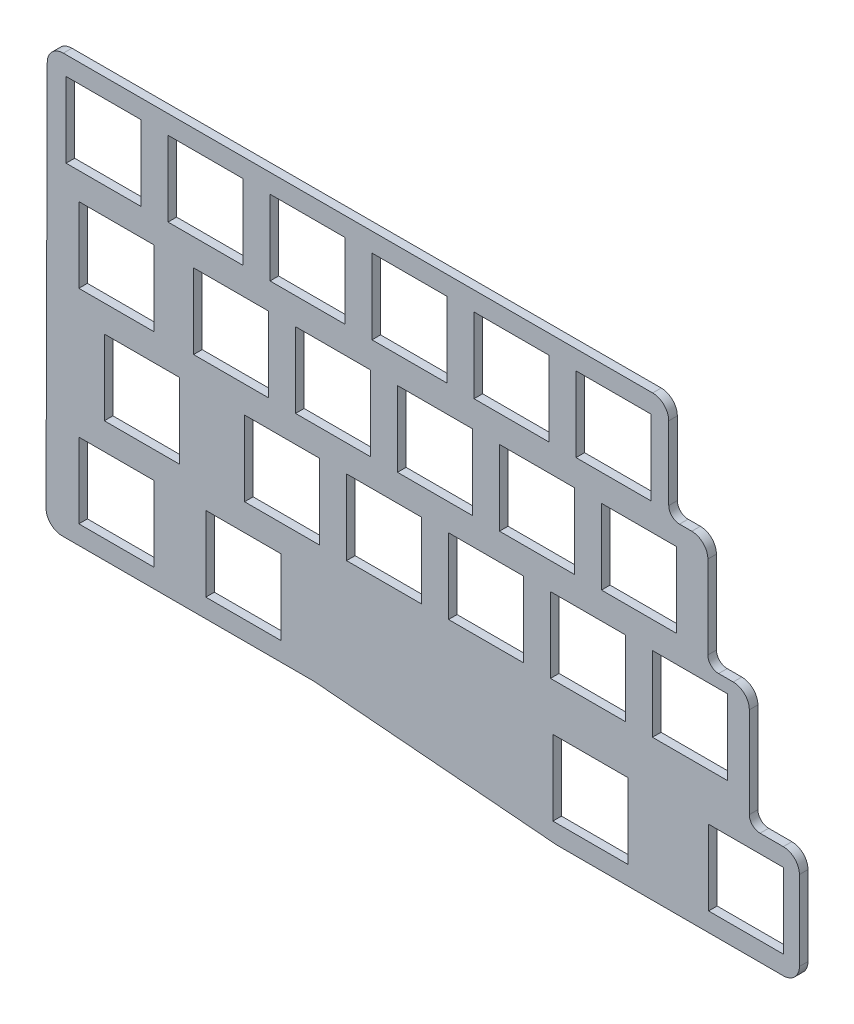
SolidWorks part; units mm, degrees
ref_plane "Front Plane" through (0, 0, 0) normal (0, 0, 1) x (1, 0, 0)
ref_plane "Top Plane" through (0, 0, 0) normal (0, 1, 0) x (1, 0, 0)
ref_plane "Right Plane" through (0, 0, 0) normal (1, 0, 0) x (0, 0, -1)
sketch "Sketch1" plane through (0, 0, 0) normal (0, 0, 1) x (1, 0, 0)
  line B0 (69.2565, 39.1549) -> (-80.7031, 39.0588)
  line B1 (9.8084, 35.5569) -> (-4.1916, 35.5569)
  line B2 (14.8084, 35.5569) -> (14.8084, 21.5569)
  line B3 (28.8084, 21.5569) -> (28.8084, 35.5569)
  line B4 (-28.1916, 35.5569) -> (-42.1916, 35.5569)
  circle B5 centre (35.1084, 34.2569) radius 1.5
  line B6 (28.8084, 35.5569) -> (14.8084, 35.5569)
  line B7 (-9.1916, 21.5569) -> (-9.1916, 35.5569)
  line B8 (-9.1916, 35.5569) -> (-23.1916, 35.5569)
  line B9 (-83.7012, 36.0684) -> (-83.9319, -35.9335)
  line B10 (-63.8166, 16.5569) -> (-77.8166, 16.5569)
  line B11 (-42.4416, 2.5569) -> (-42.4416, 16.5569)
  line B12 (-23.4416, 2.5569) -> (-23.4416, 16.5569)
  line B13 (-18.4416, 16.5569) -> (-18.4416, 2.5569)
  line B14 (-46.9416, -2.4431) -> (-46.9416, -16.4431)
  line B15 (-32.9416, -16.4431) -> (-32.9416, -2.4431)
  line B16 (5.0584, -2.4431) -> (-8.9416, -2.4431)
  line B17 (19.5584, 2.5569) -> (33.5584, 2.5569)
  line B18 (33.5584, 2.5569) -> (33.5584, 16.5569)
  line B19 (-77.8166, 16.5569) -> (-77.8166, 2.5569)
  line B20 (-8.9416, -2.4431) -> (-8.9416, -16.4431)
  line B21 (5.0584, -16.4431) -> (5.0584, -2.4431)
  line B22 (29.0584, -16.4431) -> (43.0584, -16.4431)
  line B23 (62.4422, -40.6918) -> (72.1045, -11.705)
  line B24 (10.5084, -25.2431) -> (10.5084, -39.2431)
  line B25 (-63.8166, -21.4431) -> (-77.8166, -21.4431)
  line B26 (-66.1916, 21.5569) -> (-66.1916, 35.5569)
  line B27 (-66.1916, 35.5569) -> (-80.1916, 35.5569)
  line B28 (-80.1916, 35.5569) -> (-80.1916, 21.5569)
  arc B29 (-80.7031, 39.0588) -> (-83.7012, 36.0684) centre (-80.7012, 36.0588) ccw
  arc B30 (-83.9319, -35.9335) -> (-80.932, -38.9431) centre (-80.932, -35.9431) ccw
  line B31 (-80.932, -38.9431) -> (-34.1624, -38.9431)
  arc B32 (-33.9113, -38.9537) -> (-34.1624, -38.9431) centre (-34.1624, -41.9431) ccw
  line B33 (-33.9113, -38.9537) -> (11.0831, -42.7326)
  arc B34 (11.0831, -42.7326) -> (11.3342, -42.7431) centre (11.3342, -39.7431) ccw
  line B35 (11.3342, -42.7431) -> (59.5961, -42.7431)
  arc B36 (59.5961, -42.7431) -> (62.4422, -40.6918) centre (59.5961, -39.7431) ccw
  arc B37 (72.1045, -11.705) -> (72.2584, -10.7563) centre (69.2584, -10.7563) ccw
  line B38 (72.2584, -10.7563) -> (72.2584, 36.1549)
  arc B39 (72.2584, 36.1549) -> (69.2565, 39.1549) centre (69.2584, 36.1549) ccw
  circle B40 centre (-28.1616, -22.7431) radius 1.5
  circle B41 centre (-1.4916, -27.4931) radius 1.5
  circle B42 centre (-79.3666, -9.4431) radius 1.5
  circle B43 centre (49.3584, -9.4431) radius 1.5
  circle B44 centre (-59.8916, 17.1569) radius 1.5
  line B45 (-80.1916, 21.5569) -> (-66.1916, 21.5569)
  line B46 (-61.1916, 21.5569) -> (-47.1916, 21.5569)
  line B47 (-47.1916, 21.5569) -> (-47.1916, 35.5569)
  line B48 (-47.1916, 35.5569) -> (-61.1916, 35.5569)
  line B49 (-61.1916, 35.5569) -> (-61.1916, 21.5569)
  line B50 (-42.1916, 21.5569) -> (-28.1916, 21.5569)
  line B51 (-28.1916, 21.5569) -> (-28.1916, 35.5569)
  line B52 (-42.1916, 35.5569) -> (-42.1916, 21.5569)
  line B53 (-23.1916, 21.5569) -> (-9.1916, 21.5569)
  line B54 (-23.1916, 35.5569) -> (-23.1916, 21.5569)
  line B55 (-4.1916, 21.5569) -> (9.8084, 21.5569)
  line B56 (9.8084, 21.5569) -> (9.8084, 35.5569)
  line B57 (-4.1916, 35.5569) -> (-4.1916, 21.5569)
  line B58 (14.8084, 21.5569) -> (28.8084, 21.5569)
  line B59 (-77.8166, 2.5569) -> (-63.8166, 2.5569)
  line B60 (-63.8166, 2.5569) -> (-63.8166, 16.5569)
  line B61 (-56.4416, 2.5569) -> (-42.4416, 2.5569)
  line B62 (-42.4416, 16.5569) -> (-56.4416, 16.5569)
  line B63 (-56.4416, 16.5569) -> (-56.4416, 2.5569)
  line B64 (-37.4416, 2.5569) -> (-23.4416, 2.5569)
  line B65 (-23.4416, 16.5569) -> (-37.4416, 16.5569)
  line B66 (-37.4416, 16.5569) -> (-37.4416, 2.5569)
  line B67 (-18.4416, 2.5569) -> (-4.4416, 2.5569)
  line B68 (-4.4416, 2.5569) -> (-4.4416, 16.5569)
  line B69 (-4.4416, 16.5569) -> (-18.4416, 16.5569)
  line B70 (0.5584, 2.5569) -> (14.5584, 2.5569)
  line B71 (14.5584, 2.5569) -> (14.5584, 16.5569)
  line B72 (14.5584, 16.5569) -> (0.5584, 16.5569)
  line B73 (0.5584, 16.5569) -> (0.5584, 2.5569)
  line B74 (33.5584, 16.5569) -> (19.5584, 16.5569)
  line B75 (19.5584, 16.5569) -> (19.5584, 2.5569)
  line B76 (-73.0666, -16.4431) -> (-59.0666, -16.4431)
  line B77 (-59.0666, -16.4431) -> (-59.0666, -2.4431)
  line B78 (-59.0666, -2.4431) -> (-73.0666, -2.4431)
  line B79 (-73.0666, -2.4431) -> (-73.0666, -16.4431)
  line B80 (-46.9416, -16.4431) -> (-32.9416, -16.4431)
  line B81 (-32.9416, -2.4431) -> (-46.9416, -2.4431)
  line B82 (-27.9416, -16.4431) -> (-13.9416, -16.4431)
  line B83 (-13.9416, -16.4431) -> (-13.9416, -2.4431)
  line B84 (-13.9416, -2.4431) -> (-27.9416, -2.4431)
  line B85 (-27.9416, -2.4431) -> (-27.9416, -16.4431)
  line B86 (-8.9416, -16.4431) -> (5.0584, -16.4431)
  line B87 (10.0584, -16.4431) -> (24.0584, -16.4431)
  line B88 (24.0584, -16.4431) -> (24.0584, -2.4431)
  line B89 (24.0584, -2.4431) -> (10.0584, -2.4431)
  line B90 (10.0584, -2.4431) -> (10.0584, -16.4431)
  line B91 (43.0584, -16.4431) -> (43.0584, -2.4431)
  line B92 (43.0584, -2.4431) -> (29.0584, -2.4431)
  line B93 (29.0584, -2.4431) -> (29.0584, -16.4431)
  line B94 (-77.8166, -35.4431) -> (-63.8166, -35.4431)
  line B95 (-63.8166, -35.4431) -> (-63.8166, -21.4431)
  line B96 (-77.8166, -21.4431) -> (-77.8166, -35.4431)
  line B97 (-54.1616, -35.4431) -> (-40.1616, -35.4431)
  line B98 (-40.1616, -35.4431) -> (-40.1616, -21.4431)
  line B99 (-40.1616, -21.4431) -> (-54.1616, -21.4431)
  line B100 (-54.1616, -21.4431) -> (-54.1616, -35.4431)
  line B101 (10.5084, -39.2431) -> (24.5084, -39.2431)
  line B102 (24.5084, -39.2431) -> (24.5084, -25.2431)
  line B103 (24.5084, -25.2431) -> (10.5084, -25.2431)
  line B104 (39.5084, -39.2431) -> (53.5084, -39.2431)
  line B105 (53.5084, -39.2431) -> (53.5084, -25.2431)
  line B106 (53.5084, -25.2431) -> (39.5084, -25.2431)
  line B107 (39.5084, -25.2431) -> (39.5084, -39.2431)
sketch_block_instance "switch_plate (1)-1"
sketch_block "switch_plate (1)"
extrude "Boss-Extrude1" add sketch "Sketch1" along normal blind 1.6
sketch "Sketch2" plane through (0, 0, 1.6) normal (0, 0, 1) x (1, 0, 0)
  line L0 (39.3773, 41.9719) -> (39.3773, 0)
  line L1 (39.3773, 0) -> (47.1007, 0)
  line L2 (47.1007, 0) -> (47.1007, -5.9776)
  line L3 (47.1007, -5.9776) -> (56.4332, -5.9776)
  line L4 (56.4332, -5.9776) -> (56.4332, -45.2383)
  line L5 (56.4332, -45.2383) -> (88.4532, -41.8593)
  line L6 (88.4532, -41.8593) -> (93.4412, 41.9719)
  line L7 (93.4412, 41.9719) -> (39.3773, 41.9719)
extrude "Cut-Extrude1" cut sketch "Sketch2" against normal blind 1.6
fillet "Fillet1" radius 3 4 edges at (56.4332, -42.7431, 0.8) (56.4332, -5.9776, 0.8) (47.1007, 0, 0.8) (39.3773, 39.1358, 0.8)
sketch "Sketch3" plane through (0, 0, 1.6) normal (0, 0, 1) x (1, 0, 0)
  line L1 (-81.5675, -3.6845) -> (-75.6388, -3.6845)
  line L2 (-81.5675, -3.6845) -> (-81.5675, -16.1202)
  line L3 (-81.5675, -16.1202) -> (-75.6388, -16.1202)
  line L4 (-75.6388, -3.6845) -> (-75.6388, -16.1202)
  line L5 (-62.7693, 20.1748) -> (-57.419, 20.1748)
  line L6 (-62.7693, 20.1748) -> (-62.7693, 14.2461)
  line L7 (-62.7693, 14.2461) -> (-57.419, 14.2461)
  line L8 (-57.419, 20.1748) -> (-57.419, 14.2461)
  line L9 (-30.8124, -20.169) -> (-25.1729, -20.169)
  line L10 (-30.8124, -20.169) -> (-30.8124, -26.0977)
  line L11 (-30.8124, -26.0977) -> (-25.1729, -26.0977)
  line L12 (-25.1729, -20.169) -> (-25.1729, -26.0977)
  line L13 (-4.6395, -23.1334) -> (2.0122, -23.1334)
  line L14 (-4.6395, -23.1334) -> (-4.6395, -30.5803)
  line L15 (-4.6395, -30.5803) -> (2.0122, -30.5803)
  line L16 (2.0122, -23.1334) -> (2.0122, -30.5803)
  line L17 (46.694, -7.5887) -> (52.6227, -7.5887)
  line L18 (46.694, -7.5887) -> (46.694, -13.3728)
  line L19 (46.694, -13.3728) -> (52.6227, -13.3728)
  line L20 (52.6227, -7.5887) -> (52.6227, -13.3728)
  line L21 (32.3785, 36.2256) -> (37.7287, 36.2256)
  line L22 (32.3785, 36.2256) -> (32.3785, 31.5983)
  line L23 (32.3785, 31.5983) -> (37.7287, 31.5983)
  line L24 (37.7287, 36.2256) -> (37.7287, 31.5983)
extrude "Boss-Extrude2" add sketch "Sketch3" against normal through all
sketch "Sketch4" plane through (0, 0, 1.6) normal (0, 0, 1) x (1, 0, 0)
  line L0 (47.1007, -5.9776) -> (47.1007, -21.9042)
  line L1 (47.1007, -21.9042) -> (70.2641, -21.9042)
  line L2 (70.2641, -21.9042) -> (70.2641, 0)
  line L3 (70.2641, 0) -> (47.1007, -5.9776)
extrude "Cut-Extrude2" cut sketch "Sketch4" against normal through all
fillet "Fillet2" radius 3 1 edges at (56.4332, -21.9042, 0.8)
sketch "Sketch5" plane through (0, 0, 1.6) normal (0, 0, 1) x (1, 0, 0)
  line L0 (39.3773, 20.464) -> (32.0893, 20.464)
  line L1 (39.3773, 36.1339) -> (39.3773, 0) construction
  line L2 (32.0893, 20.464) -> (32.0893, 44.034)
  line L3 (32.0893, 44.034) -> (51.3213, 44.034)
  line L4 (51.3213, 44.034) -> (39.3773, 20.464)
extrude "Cut-Extrude3" cut sketch "Sketch5" against normal through all
fillet "Fillet3" radius 3 1 edges at (32.0893, 39.1311, 0.8)
fillet "Fillet4" radius 3 1 edges at (39.3773, 20.464, 0.8)
fillet "Fillet7" radius 2 3 edges at (47.1007, -21.9042, 0.8) (39.3773, 0, 0.8) (32.0893, 20.464, 0.8)
